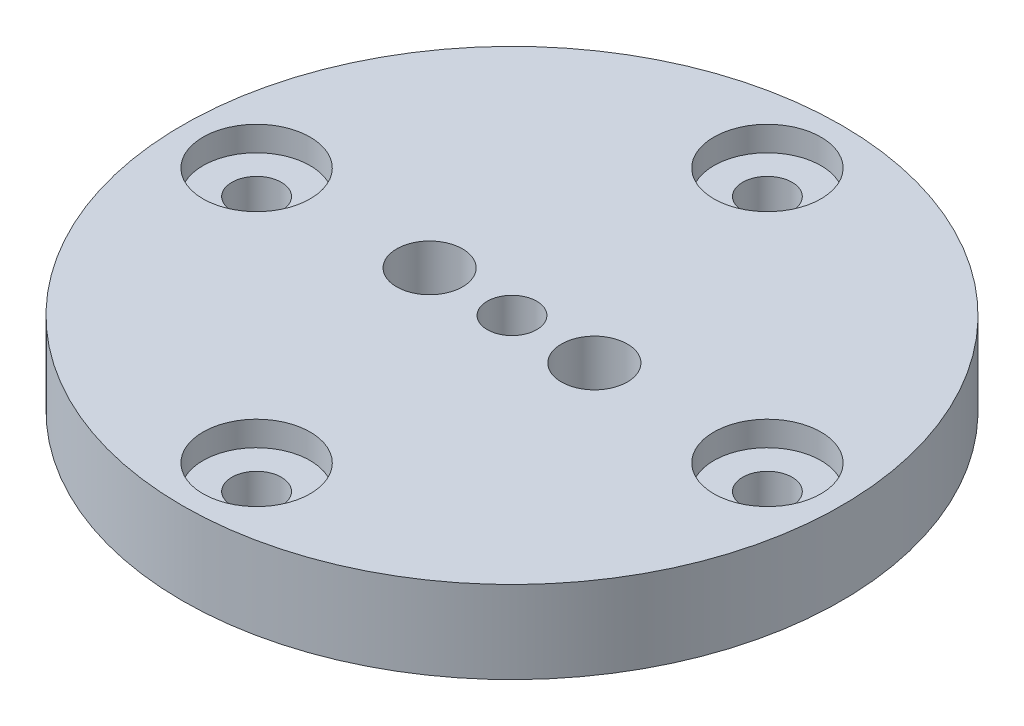
SolidWorks part; units mm, degrees
ref_plane "Front Plane" through (0, 0, 0) normal (0, 0, 1) x (1, 0, 0)
ref_plane "Top Plane" through (0, 0, 0) normal (0, 1, 0) x (1, 0, 0)
ref_plane "Right Plane" through (0, 0, 0) normal (1, 0, 0) x (0, 0, -1)
sketch "Sketch1" plane through (0, 0, 0) normal (0, 1, 0) x (1, 0, 0)
  circle A0 centre (0, 0) radius 15.5 construction
  circle A1 centre (0, 15.5) radius 1.5
  circle A2 centre (15.5, 0) radius 1.5
  circle A3 centre (0, -15.5) radius 1.5
  circle A4 centre (-15.5, 0) radius 1.5
  circle A5 centre (0, 0) radius 20
  circle A6 centre (0, 0) radius 5 construction
  circle A7 centre (-5, 0) radius 2
  circle A8 centre (5, 0) radius 2
  circle A9 centre (0, 0) radius 1.5
  point P14 (0, 0)
  dimension "D1" = 31
  dimension "D2" = 3
  dimension "D4" = 40
  dimension "D5" = 10
  dimension "D6" = 4
  dimension "D7" = 3
  dimension "D3" = 4
extrude "Boss-Extrude1" add sketch "Sketch1" along normal blind 5
sketch "Sketch2" plane through (0, 5, 0) normal (0, 1, 0) x (1, 0, 0)
  circle A0 centre (0, 0) radius 15.5 construction
  circle A1 centre (0, 15.5) radius 3.25
  circle A2 centre (15.5, 0) radius 3.25
  circle A3 centre (0, -15.5) radius 3.25
  circle A4 centre (-15.5, 0) radius 3.25
  point P15 (0, 0)
  dimension "D1" = 6.5
  dimension "D2" = 4
extrude "Cut-Extrude1" cut sketch "Sketch2" against normal blind 1.5
